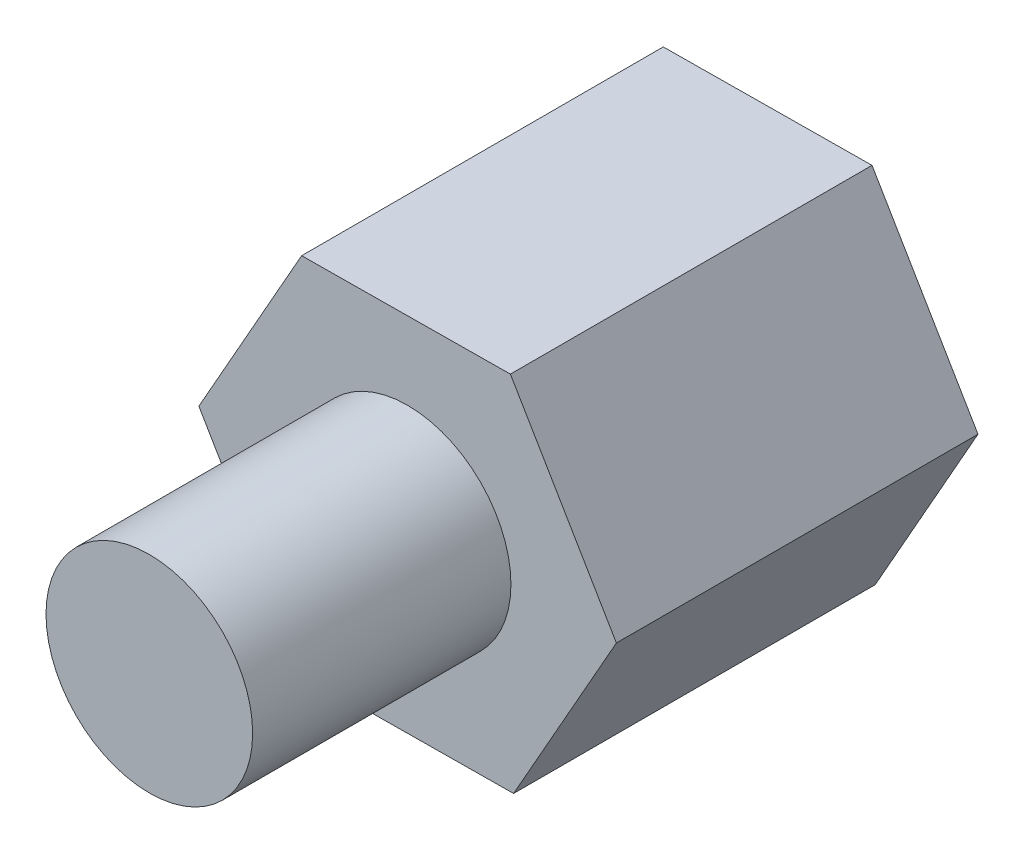
SolidWorks part; units mm, degrees
ref_plane "前视基准面" through (0, 0, 0) normal (0, 0, 1) x (1, 0, 0)
ref_plane "上视基准面" through (0, 0, 0) normal (0, 1, 0) x (1, 0, 0)
ref_plane "右视基准面" through (0, 0, 0) normal (1, 0, 0) x (0, 0, -1)
sketch "草图1" plane through (0, 0, 0) normal (0, 0, 1) x (1, 0, 0)
  line L1 (2.0515, -3.4821) -> (4.0413, 0.0356)
  line L2 (4.0413, 0.0356) -> (1.9898, 3.5177)
  line L3 (1.9898, 3.5177) -> (-2.0515, 3.4821)
  line L4 (-2.0515, 3.4821) -> (-4.0413, -0.0356)
  line L5 (-4.0413, -0.0356) -> (-1.9898, -3.5177)
  line L6 (-1.9898, -3.5177) -> (2.0515, -3.4821)
  circle A0 centre (0, 0) radius 3.5 construction
  circle A1 centre (0, 0) radius 2
extrude "凸台-拉伸1" add sketch "草图1" along normal blind 7
sketch "草图3" plane through (0, 0, 7) normal (0, 0, 1) x (1, 0, 0)
  circle A0 centre (0, 0) radius 2
extrude "凸台-拉伸2" add sketch "草图3" along normal blind 5 separate body
